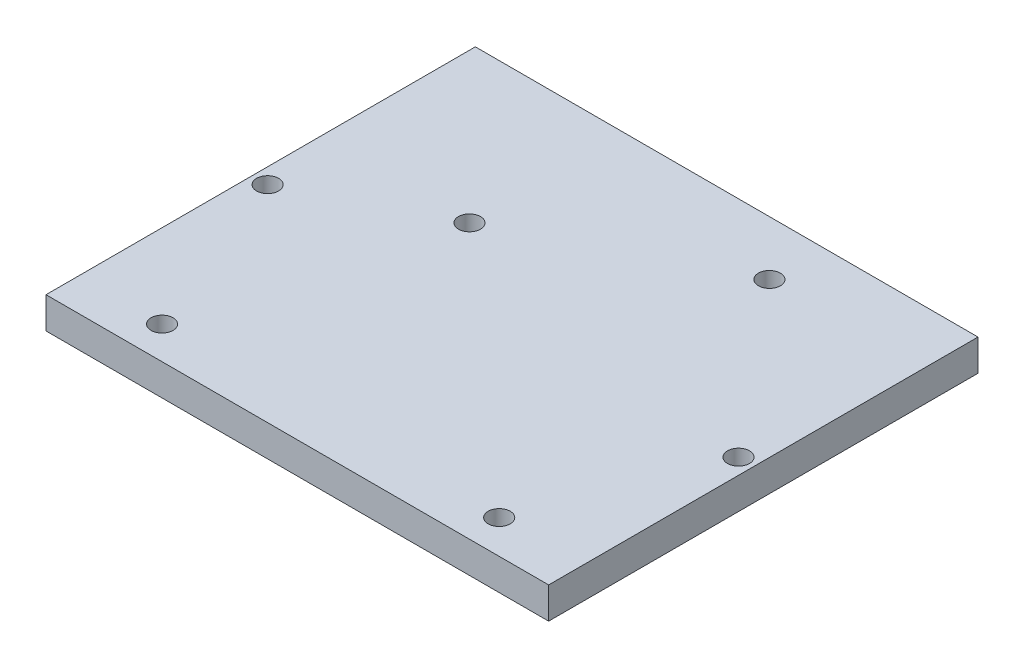
SolidWorks part; units mm, degrees
ref_plane "前视基准面" through (0, 0, 0) normal (0, 0, 1) x (1, 0, 0)
ref_plane "上视基准面" through (0, 0, 0) normal (0, 1, 0) x (1, 0, 0)
ref_plane "右视基准面" through (0, 0, 0) normal (1, 0, 0) x (0, 0, -1)
sketch "草图1" plane through (0, 0, 0) normal (0, 1, 0) x (1, 0, 0)
  line L1 (0, 0) -> (48, 0)
  line L2 (0, 0) -> (0, 41)
  line L3 (0, 41) -> (48, 41)
  line L4 (48, 0) -> (48, 41)
  circle A0 centre (7.97, 3.11) radius 1.05
  circle A1 centre (1.48, 19.68) radius 1.05
  circle A2 centre (14.28, 26.16) radius 1.05
  circle A3 centre (40.07, 3.21) radius 1.05
  circle A4 centre (46.5, 19.63) radius 1.05
  circle A5 centre (33.28, 35.8) radius 1.05
  dimension "D15" = 2.1
  dimension "D16" = 2.1
  dimension "D17" = 2.1
  dimension "D18" = 2.1
  dimension "D19" = 2.1
  dimension "D20" = 2.1
  dimension "D1" = 48
  dimension "D2" = 41
  dimension "D3" = 7.97
  dimension "D4" = 3.11
  dimension "D5" = 1.48
  dimension "D6" = 19.68
  dimension "D7" = 14.28
  dimension "D8" = 26.16
  dimension "D9" = 7.93
  dimension "D10" = 3.21
  dimension "D11" = 1.5
  dimension "D12" = 19.63
  dimension "D13" = 14.72
  dimension "D14" = 35.8
extrude "凸台-拉伸1" add sketch "草图1" along normal blind 3
